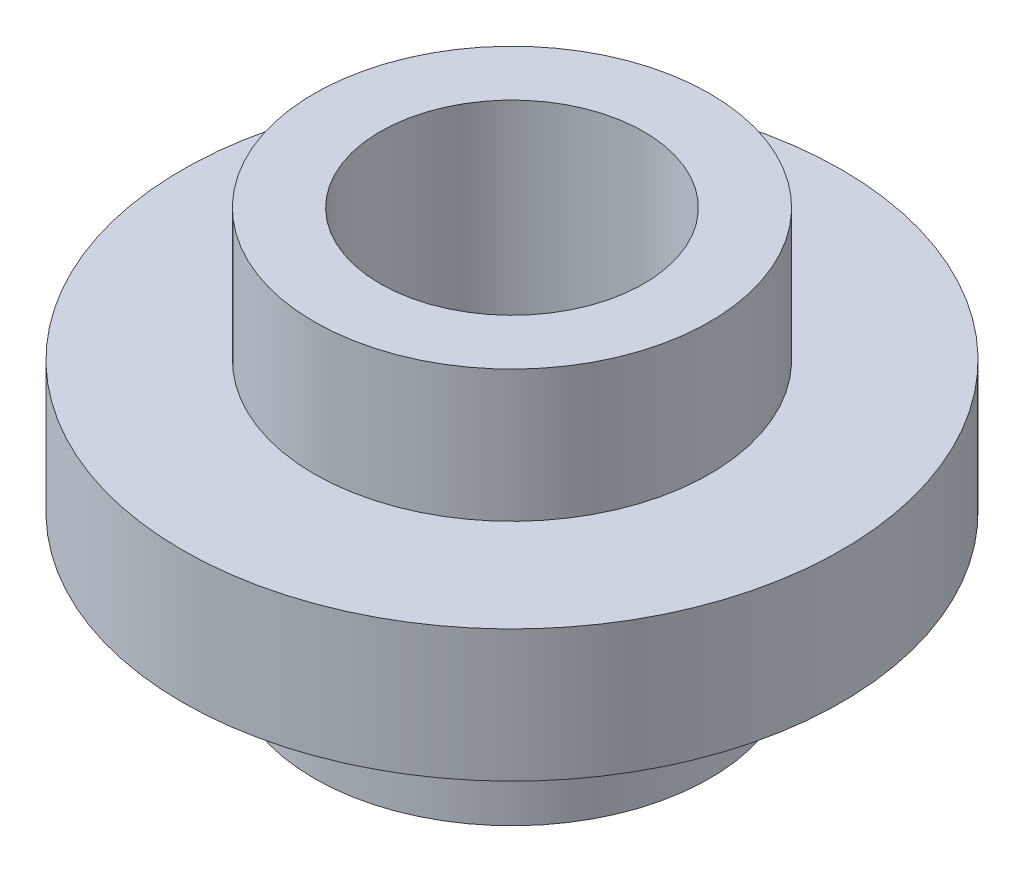
SolidWorks part; units mm, degrees
ref_plane "Front Plane" through (0, 0, 0) normal (0, 0, 1) x (1, 0, 0)
ref_plane "Top Plane" through (0, 0, 0) normal (0, 1, 0) x (1, 0, 0)
ref_plane "Right Plane" through (0, 0, 0) normal (1, 0, 0) x (0, 0, -1)
sketch "Sketch1" plane through (0, 0, 0) normal (0, 1, 0) x (1, 0, 0)
  circle A0 centre (0, 0) radius 3.175
  circle A1 centre (0, 0) radius 7.9375
  dimension "D1" = 15.875
  dimension "D2" = 6.35
extrude "Boss-Extrude1" add sketch "Sketch1" along normal blind 3.175
sketch "Sketch2" plane through (0, 3.175, 0) normal (0, 1, 0) x (1, 0, 0)
  circle A0 centre (0, 0) radius 3.175
  circle A1 centre (0, 0) radius 4.7625
  dimension "D1" = 9.525
extrude "Boss-Extrude2" add sketch "Sketch2" along normal blind 3.175 and the other way blind 6.35
